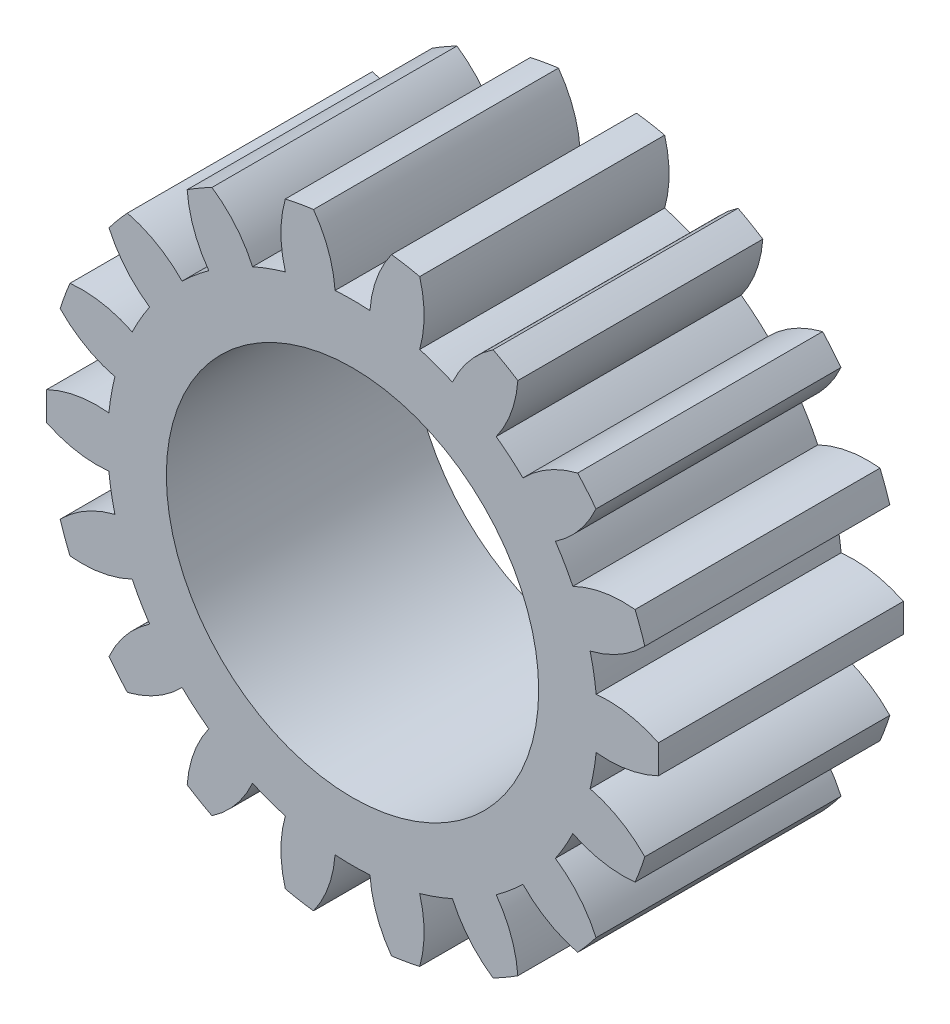
SolidWorks part; units mm, degrees
material "6061 Alloy"
ref_plane "Front Plane" through (0, 0, 0) normal (0, 0, 1) x (1, 0, 0)
ref_plane "Top Plane" through (0, 0, 0) normal (0, 1, 0) x (1, 0, 0)
ref_plane "Right Plane" through (0, 0, 0) normal (1, 0, 0) x (0, 0, -1)
sketch "Sketch1" plane through (0, 0, 0) normal (0, 0, 1) x (1, 0, 0)
  circle A0 centre (0, 0) radius 7.9375
  dimension "D1" = 15.875
extrude "Outer Circle" add sketch "Sketch1" along normal blind 6.35
sketch "Sketch2" plane through (0, 0, 6.35) normal (0, 0, 1) x (1, 0, 0)
  line L0 (0.625, 7.1437) -> (-0.625, 7.1437) construction
  line L1 (1.856, 6.9267) -> (0.625, 7.1437) construction
  line L2 (0, 7.1437) -> (0, 0) construction
  line L3 (0, 0) -> (1.2405, 7.0352) construction
  line L4 (-0.8955, 7.8868) -> (0, 5.4266) construction
  line L5 (0, 5.4266) -> (0.8955, 7.8868) construction
  line L6 (-0.4522, 6.3339) -> (0, 0) construction
  circle A0 centre (0, 0) radius 6.35 construction
  circle A1 centre (0, 0) radius 7.1438 construction
  arc A2 (-0.4522, 6.3339) -> (0.4522, 6.3339) centre (0, 0) cw
  arc A3 (-1.0115, 7.8728) -> (1.0115, 7.8728) centre (0, 0) cw
  circle A4 centre (0, 0) radius 7.9375 construction
  arc A5 (-1.0115, 7.8728) -> (-0.4522, 6.3339) centre (-3.4353, 6.1209) cw
  arc A6 (0.4522, 6.3339) -> (1.0115, 7.8728) centre (3.4353, 6.1209) cw
  point P7 (0, 7.1437)
  point P10 (1.2405, 7.0352)
  point P17 (0, 6.35)
  point P19 (0, 7.9375)
  dimension "D1" = 12.7
  dimension "D2" = 14.2875
  dimension "D3" = 10
  dimension "D4" = 20
extrude "Tooth Cut" cut sketch "Sketch2" against normal through all
pattern_circular "Teeth Pattern" count 18 over 360 about axis through (0, 0, 0) along (0, 0, 1) of "Tooth Cut"
ref_plane "Plane1" through (0, 0, 3.175) normal (0, 0, 1) x (1, 0, 0)
sketch "Pitch Diameter" plane through (0, 0, 3.175) normal (0, 0, 1) x (1, 0, 0)
  circle A0 centre (0, 0) radius 7.1438 construction
  circle A1 centre (0, 0) radius 7.1438
  circle A2 centre (0, 0) radius 4.826
  dimension "D1" = 9.652
extrude "Cut-Extrude1" cut sketch "Pitch Diameter" against normal through all and the other way through all contours A2
equation "\"No. of Teeth\"= 18"
equation "\"Module\"= 1 / 32'Inverse of Pitch"
equation "\"D1@Sketch1\"=(\"No. of Teeth\"+2)*\"Module\""
equation "\"D1@Sketch2\"=(\"No. of Teeth\"-2)*\"Module\""
equation "\"D2@Sketch2\"= \"No. of Teeth\" * \"Module\"'Pitch Diameter"
equation "\"D3@Sketch2\"=180/\"No. of Teeth\""
equation "\"D1@Teeth Pattern\" = \"No. of Teeth\""
